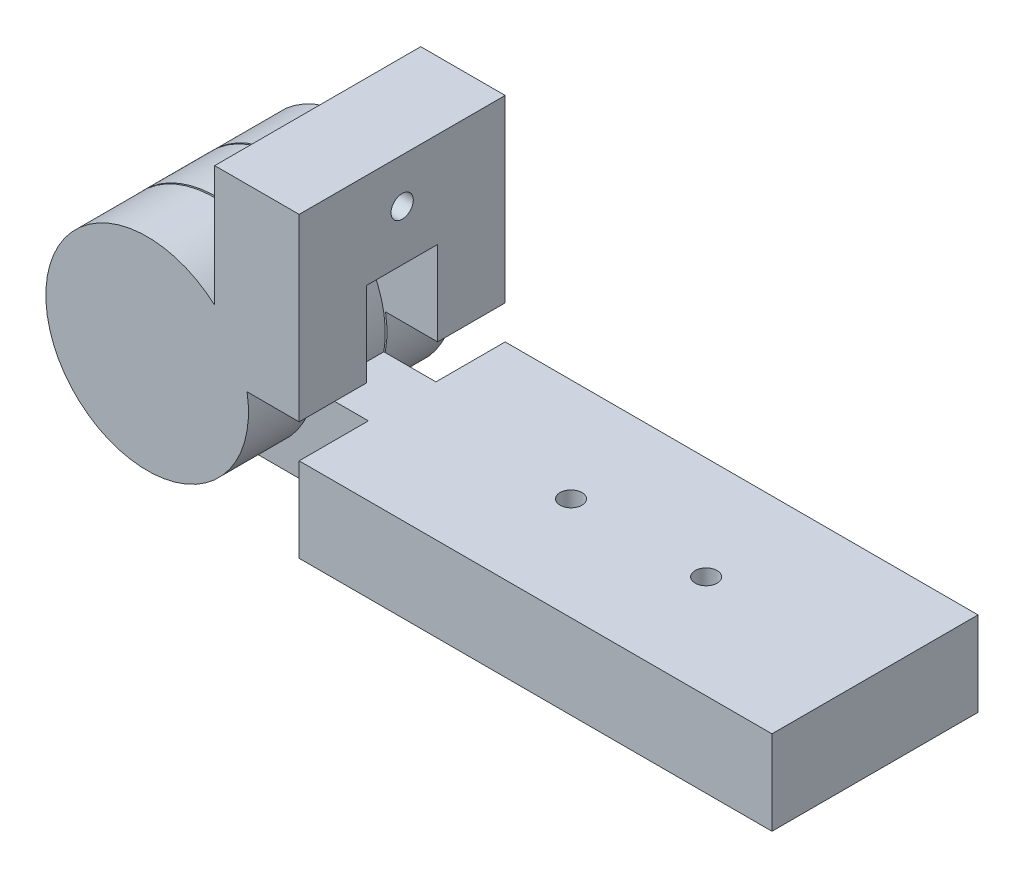
SolidWorks part; units mm, degrees
ref_plane "Front Plane" through (0, 0, 0) normal (0, 0, 1) x (1, 0, 0)
ref_plane "Top Plane" through (0, 0, 0) normal (0, 1, 0) x (1, 0, 0)
ref_plane "Right Plane" through (0, 0, 0) normal (1, 0, 0) x (0, 0, -1)
sketch "Sketch1" plane through (0, 0, 0) normal (0, 0, 1) x (1, 0, 0)
  circle A0 centre (-73.025, -41.275) radius 19.05
  circle A2 centre (-73.025, -41.275) radius 2.8702 construction
  dimension "D1" = 38.1
extrude "Boss-Extrude1" add sketch "Sketch1" along normal mid plane 12.7
sketch "Sketch2" plane through (0, 0, 6.35) normal (0, 0, 1) x (1, 0, 0)
  line L0 (-54.2414, -44.45) -> (44.45, -44.45)
  line L1 (44.45, -44.45) -> (44.45, -60.325)
  line L2 (44.45, -60.325) -> (-73.025, -60.325)
  line L3 (44.45, -44.45) -> (-44.45, -44.45) construction
  line L5 (44.45, 38.1) -> (44.45, -38.1) construction
  circle A0 centre (-73.025, -41.275) radius 19.05 construction
  arc A1 (-73.025, -60.325) -> (-54.2414, -44.45) centre (-73.025, -41.275) ccw
extrude "Boss-Extrude2" add sketch "Sketch2" against normal up to surface (12.7 mm away) up to face at (-53.975, -41.275, -6.35)
sketch "Sketch3" plane through (0, 0, 6.35) normal (0, 0, 1) x (1, 0, 0)
  circle A0 centre (-73.025, -41.275) radius 6.35
  dimension "D1" = 12.7
extrude "Cut-Extrude1" cut sketch "Sketch3" against normal through all
sketch "Sketch4" plane through (0, 0, 0) normal (0, 0, 1) x (1, 0, 0)
  circle A0 centre (-73.025, -41.275) radius 5.715
  dimension "D1" = 11.43
extrude "Boss-Extrude3" add sketch "Sketch4" against normal mid plane 13.335 separate body
sketch "Sketch5" plane through (0, 0, 6.6675) normal (0, 0, 1) x (1, 0, 0)
  circle A0 centre (-73.025, -41.275) radius 19.05
  arc A1 (-54.2414, -44.45) -> (-73.025, -60.325) centre (-73.025, -41.275) ccw construction
extrude "Boss-Extrude4" add sketch "Sketch5" along normal blind 12.7
sketch "Sketch6" plane through (0, 0, 19.3675) normal (0, 0, 1) x (1, 0, 0)
  line L0 (-44.45, -38.1) -> (-44.45, 38.1)
  line L1 (-44.45, 38.1) -> (-44.45, 24.5485) construction
  line L2 (-44.45, 38.1) -> (-60.325, 38.1)
  line L3 (-60.325, 38.1) -> (-60.325, -27.076)
  line L4 (-44.45, -38.1) -> (-54.2414, -38.1)
  line L5 (-44.45, -38.1) -> (44.45, -38.1) construction
  circle A1 centre (-73.025, -41.275) radius 19.05 construction
  arc A2 (-60.325, -27.076) -> (-54.2414, -38.1) centre (-73.025, -41.275) cw
  dimension "D1" = 15.875
extrude "Boss-Extrude5" add sketch "Sketch6" against normal up to surface (12.7 mm away) up to face at (-67.31, -41.275, 6.6675)
ref_plane "Silo Hinge Mid Plane" through (0, 0, 0) normal (0, 0, 1) x (1, 0, 0)
mirror "Mirror1" about plane through (0, 0, 0) normal (0, 0, 1) of "Boss-Extrude5", "Boss-Extrude4"
sketch "Sketch7" plane through (0, 0, 6.6675) normal (0, 0, -1) x (-1, 0, 0)
  line L0 (60.325, -27.076) -> (60.325, 38.1) construction
  line L1 (44.45, 38.1) -> (60.325, 38.1)
  line L2 (44.45, 38.1) -> (44.45, -22.225)
  line L3 (44.45, -22.225) -> (60.325, -22.225)
  line L4 (60.325, 38.1) -> (60.325, -22.225)
  line L5 (98.7602, -22.225) -> (64.3668, -22.225) construction
  arc A0 (54.2414, -38.1) -> (60.325, -27.076) centre (73.025, -41.275) ccw construction
extrude "Boss-Extrude6" add sketch "Sketch7" along normal up to surface (13.335 mm away)
sketch "Sketch8" plane through (0, 0, 6.35) normal (0, 0, 1) x (1, 0, 0)
  line L0 (44.45, -44.45) -> (-54.2414, -44.45) construction
  line L1 (44.45, -60.325) -> (-44.45, -60.325)
  line L2 (44.45, -60.325) -> (44.45, -44.45)
  line L3 (44.45, -44.45) -> (-44.45, -44.45)
  line L4 (-44.45, -60.325) -> (-44.45, -44.45)
extrude "Boss-Extrude7" add sketch "Sketch8" along normal up to surface and the other way up to surface
sketch "Sketch9" [suppressed] plane through (0, 0, -6.35) normal (0, 0, -1) x (-1, 0, 0)
  line L4 (60.325, -27.076) -> (60.325, 38.1)
  line L5 (60.325, 38.1) -> (44.45, 38.1)
  line L6 (44.45, 38.1) -> (44.45, -38.1)
  line L7 (44.45, -38.1) -> (54.2414, -38.1)
  line L8 (60.325, -27.076) -> (60.325, 38.1)
  line L9 (60.325, 38.1) -> (44.45, 38.1)
  line L10 (44.45, 38.1) -> (44.45, -38.1)
  line L11 (44.45, -38.1) -> (54.2414, -38.1)
  arc A1 (54.2414, -38.1) -> (60.325, -27.076) centre (73.025, -41.275) ccw
  arc A2 (54.2414, -38.1) -> (60.325, -27.076) centre (73.025, -41.275) ccw
  dimension "D1" = 0
extrude "Cut-Extrude2" [suppressed] cut sketch "Sketch9" along normal through all
mirror "Mirror2" [suppressed] about plane through (0, 0, 0) normal (0, 0, 1)
sketch "Sketch10" [suppressed] plane through (0, 0, -6.35) normal (0, 0, -1) x (-1, 0, 0)
  line L1 (44.45, 38.1) -> (60.325, 38.1)
  line L2 (44.45, 38.1) -> (44.45, -22.225)
  line L3 (44.45, -22.225) -> (60.325, -22.225)
  line L4 (60.325, 38.1) -> (60.325, -22.225)
extrude "Cut-Extrude3" [suppressed] cut sketch "Sketch10" against normal through all
sketch "Sketch11" [suppressed] plane through (0, 0, -6.35) normal (0, 0, -1) x (-1, 0, 0)
  circle A0 centre (73.025, -41.275) radius 6.0275
extrude "Cut-Extrude4" [suppressed] cut sketch "Sketch11" against normal through all
sketch "Sketch12" [suppressed] plane through (0, 0, -6.35) normal (0, 0, -1) x (-1, 0, 0)
  circle A0 centre (73.025, -41.275) radius 6.35
  circle A1 centre (73.025, -41.275) radius 1.5875
  circle A2 centre (73.025, -41.275) radius 6.35 construction
  dimension "D1" = 3.175
extrude "Boss-Extrude8" [suppressed] add sketch "Sketch12" against normal up to surface (12.7 mm away)
sketch "Sketch13" [suppressed] plane through (0, 0, -6.35) normal (0, 0, -1) x (-1, 0, 0)
  line L0 (54.2414, -44.45) -> (44.45, -44.45) construction
  line L1 (44.45, -44.45) -> (44.45, -60.325) construction
  line L2 (44.45, -60.325) -> (73.025, -60.325) construction
  line L3 (54.2414, -44.45) -> (44.45, -44.45)
  line L4 (44.45, -44.45) -> (44.45, -60.325)
  line L5 (44.45, -60.325) -> (73.025, -60.325)
  arc A0 (54.2414, -38.1) -> (60.325, -27.076) centre (73.025, -41.275) ccw construction
  arc A1 (54.2414, -38.1) -> (60.325, -27.076) centre (73.025, -41.275) ccw
  arc A2 (60.325, -27.076) -> (54.2414, -38.1) centre (73.025, -41.275) ccw
extrude "Cut-Extrude5" [suppressed] cut sketch "Sketch13" against normal up to surface and the other way up to surface
sketch "Sketch14" [suppressed] plane through (0, 0, -19.3675) normal (0, 0, -1) x (-1, 0, 0)
  line L1 (-44.45, -44.45) -> (44.45, -44.45)
  line L2 (-44.45, -44.45) -> (-44.45, -60.325)
  line L3 (-44.45, -60.325) -> (44.45, -60.325)
  line L4 (44.45, -44.45) -> (44.45, -60.325)
extrude "Cut-Extrude6" [suppressed] cut sketch "Sketch14" against normal through all
sketch "Sketch15" [suppressed] plane through (0, 0, -19.3675) normal (0, 0, -1) x (-1, 0, 0)
  circle A0 centre (73.025, -41.275) radius 1.5875
  arc A1 (54.2414, -38.1) -> (60.325, -27.076) centre (73.025, -41.275) ccw construction
  dimension "D1" = 3.175
extrude "Cut-Extrude7" [suppressed] cut sketch "Sketch15" against normal through all
sketch "Sketch16" plane through (-60.325, 0, 0) normal (-1, 0, 0) x (0, 0, 1)
  line L0 (0, -20.955) -> (0, 20.955) construction
  line L1 (0, 0) -> (0, 48.408) construction
  line L2 (0, 0) -> (40.8974, 0) construction
  circle A0 centre (0, 12.7) radius 2.0955
  circle A1 centre (0, -12.7) radius 2.0955
  dimension "D1" = 4.191
  dimension "D2" = 25.4
extrude "Cut-Extrude8" cut sketch "Sketch16" against normal through all
sketch "Sketch17" plane through (0, -44.45, 0) normal (0, 1, 0) x (1, 0, 0)
  line L0 (0, 0) -> (0, 11.213) construction
  line L2 (0, 0) -> (4.8614, 0) construction
  circle A0 centre (-12.7, 0) radius 2.0638
  circle A1 centre (12.7, 0) radius 2.0638
  dimension "D1" = 4.1275
  dimension "D2" = 25.4
extrude "Cut-Extrude9" cut sketch "Sketch17" against normal through all
fillet "Fillet1" [suppressed] radius 1.27
fillet "Fillet2" [suppressed] radius 1.27
sketch "Sketch20" plane through (-60.325, 0, 0) normal (-1, 0, 0) x (0, 0, 1)
  line L0 (19.3675, 38.1) -> (19.3675, -27.076) construction
  line L1 (-19.3675, 38.1) -> (19.3675, 38.1)
  line L2 (-19.3675, 38.1) -> (-19.3675, -4.318)
  line L3 (-19.3675, -4.318) -> (19.3675, -4.318)
  line L4 (19.3675, 38.1) -> (19.3675, -4.318)
  dimension "D1" = 42.418
extrude "Cut-Extrude13" cut sketch "Sketch20" against normal through all
